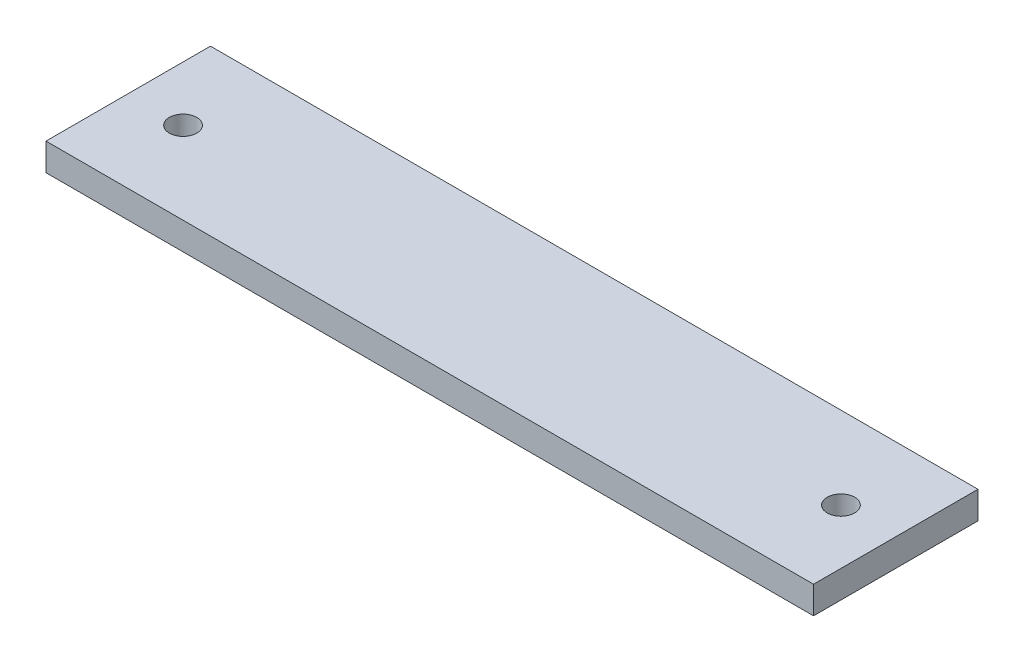
SolidWorks part; units mm, degrees
ref_plane "Front Plane" through (0, 0, 0) normal (0, 0, 1) x (1, 0, 0)
ref_plane "Top Plane" through (0, 0, 0) normal (0, 1, 0) x (1, 0, 0)
ref_plane "Right Plane" through (0, 0, 0) normal (1, 0, 0) x (0, 0, -1)
sketch "Sketch1" plane through (0, 0, 0) normal (0, 1, 0) x (1, 0, 0)
  line L0 (-66.8548, 1.5726) -> (73.1452, 1.5726) construction
  line L1 (-66.8548, 16.5726) -> (73.1452, 16.5726)
  line L2 (-66.8548, 16.5726) -> (-66.8548, -13.4274)
  line L3 (-66.8548, -13.4274) -> (73.1452, -13.4274)
  line L4 (73.1452, 16.5726) -> (73.1452, -13.4274)
  line L5 (3.1452, 16.5726) -> (3.1452, -13.4274) construction
  circle A0 centre (-56.8548, 1.5726) radius 2.5
  circle A1 centre (63.1452, 1.5726) radius 2.5
  dimension "D3" = 5
  dimension "D1" = 30
  dimension "D2" = 140
  dimension "D4" = 10
extrude "Boss-Extrude1" add sketch "Sketch1" along normal blind 5
